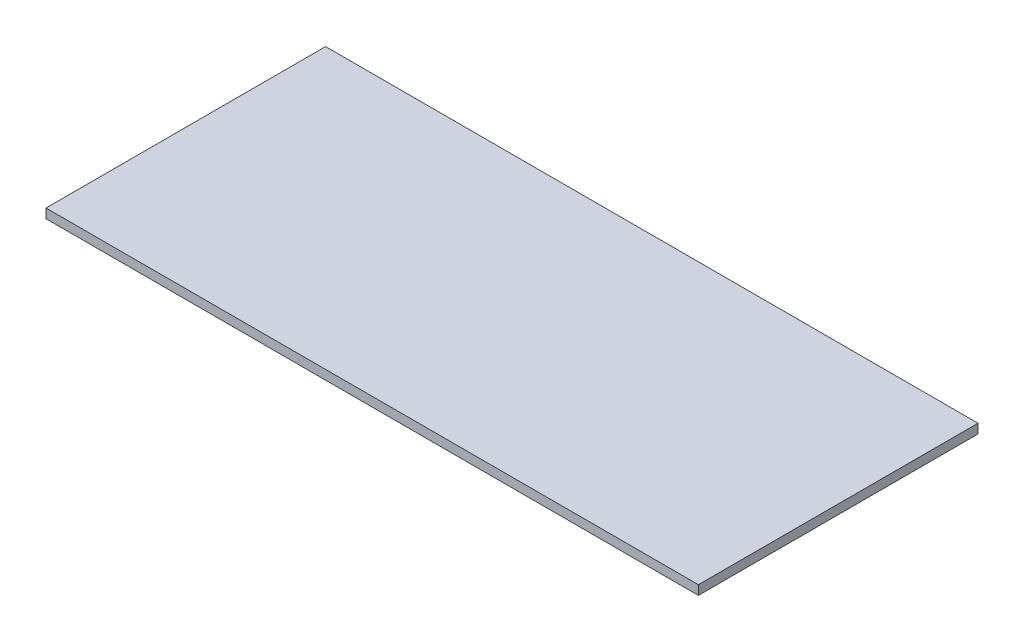
SolidWorks part; units mm, degrees
ref_plane "Alzado" through (0, 0, 0) normal (0, 0, 1) x (1, 0, 0)
ref_plane "Planta" through (0, 0, 0) normal (0, 1, 0) x (1, 0, 0)
ref_plane "Vista lateral" through (0, 0, 0) normal (1, 0, 0) x (0, 0, -1)
sketch "Croquis2" plane through (0, 0, 0) normal (0, 1, 0) x (1, 0, 0)
  line L1 (-350, -150) -> (350, -150)
  line L2 (-350, -150) -> (-350, 150)
  line L3 (-350, 150) -> (350, 150)
  line L4 (350, -150) -> (350, 150)
  line L5 (-350, -150) -> (350, 150) construction
  line L6 (-350, 150) -> (350, -150) construction
  point P0 (0, 0)
  dimension "D1" = 700
  dimension "D2" = 300
extrude "Saliente-Extruir1" add sketch "Croquis2" along normal blind 10
